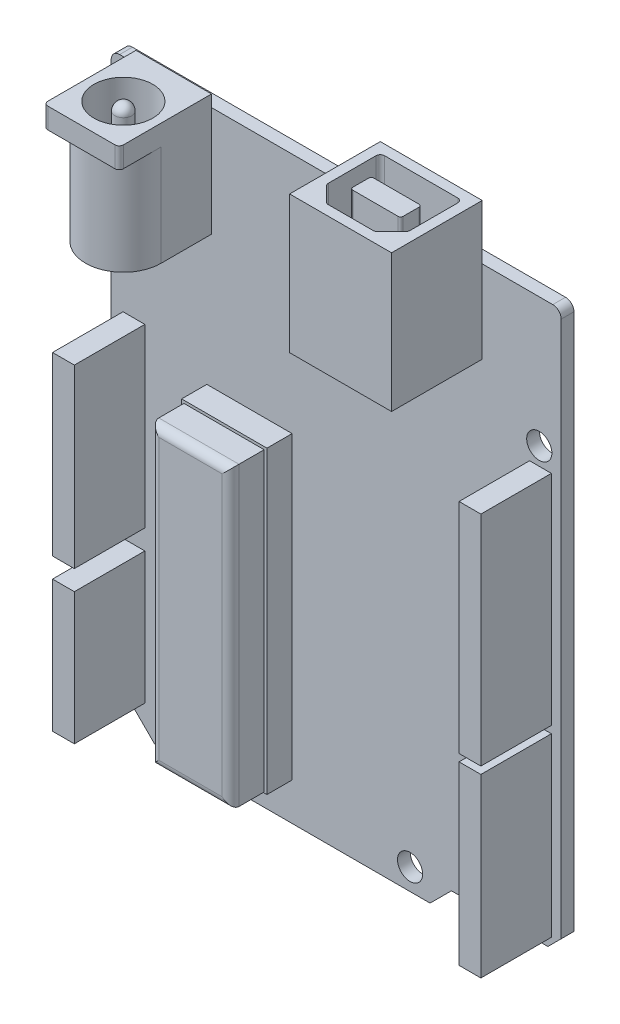
SolidWorks part; units mm, degrees
ref_plane "Plano frontal" through (0, 0, 0) normal (0, 0, 1) x (1, 0, 0)
ref_plane "Plano superior" through (0, 0, 0) normal (0, 1, 0) x (1, 0, 0)
ref_plane "Plano direito" through (0, 0, 0) normal (1, 0, 0) x (0, 0, -1)
sketch "Esboço1" plane through (0, 0, 0) normal (0, 0, 1) x (1, 0, 0)
  line L0 (391.5814, 45.9943) -> (391.5814, -648.0057) construction
  line L1 (25.8, 34.15) -> (-25.8, 34.15)
  line L2 (26.8, 33.15) -> (26.8, -30.7774)
  line L3 (-24.164, -32.36) -> (-25.8, -32.36)
  line L4 (-26.8, 33.15) -> (-26.8, -31.36)
  line L6 (-24.164, -32.36) -> (-21.6183, -34.9057)
  line L7 (11.1815, -34.9057) -> (-21.6183, -34.9057)
  line L10 (90.4669, 304.2448) -> (571.8003, 304.2448) construction
  line L11 (-23.855, 35.553) -> (-14.8521, 35.553)
  line L12 (-23.855, 35.553) -> (-23.855, 21.089)
  line L13 (-23.855, 21.089) -> (-14.8521, 21.089)
  line L14 (-14.8521, 35.553) -> (-14.8521, 21.089)
  line L15 (17.3958, 40.6929) -> (5.2524, 40.6929)
  line L16 (17.3958, 40.6929) -> (17.3958, 24.3152)
  line L17 (17.3958, 24.3152) -> (5.2524, 24.3152)
  line L18 (5.2524, 40.6929) -> (5.2524, 24.3152)
  line L19 (13.7272, -32.36) -> (11.1815, -34.9057)
  line L20 (25.2175, -32.36) -> (13.7272, -32.36)
  line L21 (26.8, -30.7774) -> (25.2175, -32.36)
  circle A0 centre (-24.164, 19.9912) radius 1.5
  circle A1 centre (24.1898, 18.7701) radius 1.5
  arc A2 (-26.8, -31.36) -> (-25.8, -32.36) centre (-25.8, -31.36) ccw
  circle A3 centre (-19.1491, -32.36) radius 1.5
  arc A4 (25.8, 34.15) -> (26.8, 33.15) centre (25.8, 33.15) cw
  arc A5 (-25.8, 34.15) -> (-26.8, 33.15) centre (-25.8, 33.15) ccw
  circle A6 centre (8.8002, -32.36) radius 1.5
  point P0 (0, 0)
  point P18 (26.8, 34.15)
  point P21 (-26.8, 34.15)
  dimension "D6" = 3
  dimension "D7" = 3
  dimension "D8" = 3
  dimension "D9" = 3
  dimension "D15" = 1
  dimension "D2" = 135
  dimension "D5" = 1
  dimension "D1" = 53.6
  dimension "D3" = 135
  dimension "D4" = 135
sketch "Esboço2" plane through (0, 0, 0) normal (0, 0, 1) x (1, 0, 0)
  line L0 (26.8, -30.7774) -> (25.2175, -32.36)
  line L1 (25.2175, -32.36) -> (13.7272, -32.36)
  line L2 (13.7272, -32.36) -> (11.1815, -34.9057)
  line L3 (11.1815, -34.9057) -> (-21.6183, -34.9057)
  line L4 (-21.6183, -34.9057) -> (-24.164, -32.36)
  line L5 (-24.164, -32.36) -> (-25.8, -32.36)
  line L7 (-26.8, -31.36) -> (-26.8, 33.15)
  line L9 (-25.8, 34.15) -> (25.8, 34.15)
  line L11 (26.8, 33.15) -> (26.8, -30.7774)
  arc A0 (26.8, 33.15) -> (25.8, 34.15) centre (25.8, 33.15) ccw
  arc A1 (-26.8, 33.15) -> (-25.8, 34.15) centre (-25.8, 33.15) cw
  arc A2 (-26.8, -31.36) -> (-25.8, -32.36) centre (-25.8, -31.36) ccw
  circle A3 centre (24.1898, 18.7701) radius 1.5
  circle A4 centre (-24.164, 19.9912) radius 1.5
  circle A5 centre (-19.1491, -32.36) radius 1.5
  circle A6 centre (8.8002, -32.36) radius 1.5
  dimension "D1" = 1
extrude "Ressalto-extrusão1" add sketch "Esboço2" along normal blind 1.52
sketch "Esboço3" plane through (0, 0, 1.52) normal (0, 0, 1) x (1, 0, 0)
  line L1 (-14.8521, 35.553) -> (-23.855, 35.553)
  line L2 (-14.8521, 35.553) -> (-14.8521, 21.089)
  line L3 (-14.8521, 21.089) -> (-23.855, 21.089)
  line L4 (-23.855, 35.553) -> (-23.855, 21.089)
extrude "Ressalto-extrusão2" add sketch "Esboço3" along normal blind 11
sketch "Esboço4" plane through (0, 0, 1.52) normal (0, 0, 1) x (1, 0, 0)
  line L1 (23.0345, -31.2018) -> (25.6345, -31.2018)
  line L2 (23.0345, -31.2018) -> (23.0345, -10.2018)
  line L3 (23.0345, -10.2018) -> (25.6345, -10.2018)
  line L4 (25.6345, -31.2018) -> (25.6345, -10.2018)
  line L8 (23.0345, -9.3418) -> (25.6345, -9.3418)
  line L9 (23.0345, -9.3418) -> (23.0345, 16.6582)
  line L10 (23.0345, 16.6582) -> (25.6345, 16.6582)
  line L11 (25.6345, -9.3418) -> (25.6345, 16.6582)
  line L13 (-25.392, 7.8156) -> (-22.792, 7.8156)
  line L14 (-25.392, 7.8156) -> (-25.392, -13.1844)
  line L15 (-25.392, -13.1844) -> (-22.792, -13.1844)
  line L16 (-22.792, 7.8156) -> (-22.792, -13.1844)
  line L17 (-22.792, -15.5599) -> (-25.392, -15.5599)
  line L18 (-22.792, -15.5599) -> (-22.792, -31.2599)
  line L19 (-22.792, -31.2599) -> (-25.392, -31.2599)
  line L20 (-25.392, -15.5599) -> (-25.392, -31.2599)
  dimension "D1" = 2.6
  dimension "D2" = 2.6
  dimension "D3" = 2.6
  dimension "D4" = 2.6
  dimension "D5" = 21
  dimension "D6" = 26
  dimension "D7" = 0.86
  dimension "D8" = 0
  dimension "D9" = 15.7
  dimension "D10" = 21
extrude "Ressalto-extrusão3" add sketch "Esboço4" along normal blind 8.4
sketch "Esboço5" plane through (0, 21.089, 0) normal (0, -1, 0) x (1, 0, 0)
  line L0 (-19.3536, 12.52) -> (-19.3536, 12.0214) construction
  line L3 (-14.8521, 7.52) -> (-14.8521, 12.52)
  line L5 (-14.8521, 12.52) -> (-23.855, 12.52)
  line L6 (-23.855, 12.52) -> (-23.855, 7.52)
  arc A0 (-14.8521, 7.52) -> (-23.855, 7.52) centre (-19.3536, 7.52) ccw
extrude "Corte-extrusão1" cut sketch "Esboço5" against normal blind 12
sketch "Esboço6" plane through (0, 35.553, 0) normal (0, -1, 0) x (1, 0, 0)
  circle A0 centre (-19.3536, 7.52) radius 3.5014
  circle A1 centre (-19.3536, 7.52) radius 1
  dimension "D1" = 7.0028
  dimension "D2" = 2
extrude "Corte-extrusão2" cut sketch "Esboço6" along normal blind 12
fillet "Filete1" radius 1 1 edges at (-19.3536, 35.553, 6.52)
fillet "Filete2" radius 0.5 2 edges at (-23.855, 34.321, 12.52) (-14.8521, 34.321, 12.52)
sketch "Esboço7" plane through (0, 0, 1.52) normal (0, 0, 1) x (1, 0, 0)
  line L1 (17.3958, 40.6929) -> (5.2524, 40.6929)
  line L2 (17.3958, 40.6929) -> (17.3958, 24.3152)
  line L3 (17.3958, 24.3152) -> (5.2524, 24.3152)
  line L4 (5.2524, 40.6929) -> (5.2524, 24.3152)
extrude "Ressalto-extrusão4" add sketch "Esboço7" along normal blind 10.8
sketch "Esboço8" plane through (0, 0, 1.52) normal (0, 0, -1) x (-1, 0, 0)
  line L0 (25.8, 34.15) -> (-25.8, 34.15) construction
  line L3 (0, 34.15) -> (0, -38.2715) construction
sketch "Esboço9" plane through (0, 40.6929, 0) normal (0, 1, 0) x (1, 0, 0)
  line L0 (17.3958, -12.32) -> (5.2524, -1.52) construction
  line L1 (17.3958, -12.32) -> (5.2524, -12.32) construction
  line L2 (6.9524, -2.72) -> (15.6958, -2.72)
  line L3 (6.4524, -3.22) -> (6.4524, -8.9129)
  line L4 (8.6595, -11.12) -> (13.9887, -11.12)
  line L5 (16.1958, -3.22) -> (16.1958, -8.9129)
  line L6 (6.4524, -2.72) -> (16.1958, -11.12) construction
  line L7 (6.4524, -11.12) -> (16.1958, -2.72) construction
  line L8 (5.2524, -12.32) -> (5.2524, -1.52) construction
  line L9 (14.3423, -10.9736) -> (16.0494, -9.2664)
  line L10 (14.0241, -8.17) -> (8.6241, -8.17)
  line L11 (14.3241, -7.87) -> (14.3241, -5.97)
  line L12 (14.0241, -5.67) -> (8.6241, -5.67)
  line L13 (8.3241, -7.87) -> (8.3241, -5.97)
  line L14 (14.3241, -8.17) -> (8.3241, -5.67) construction
  line L15 (14.3241, -5.67) -> (8.3241, -8.17) construction
  line L16 (6.5988, -9.2664) -> (8.3059, -10.9736)
  arc A0 (8.6241, -8.17) -> (8.3241, -7.87) centre (8.6241, -7.87) cw
  arc A1 (8.6241, -5.67) -> (8.3241, -5.97) centre (8.6241, -5.97) ccw
  arc A2 (14.3241, -5.97) -> (14.0241, -5.67) centre (14.0241, -5.97) ccw
  arc A3 (14.0241, -8.17) -> (14.3241, -7.87) centre (14.0241, -7.87) ccw
  arc A4 (6.9524, -2.72) -> (6.4524, -3.22) centre (6.9524, -3.22) ccw
  arc A5 (15.6958, -2.72) -> (16.1958, -3.22) centre (15.6958, -3.22) cw
  arc A6 (6.5988, -9.2664) -> (6.4524, -8.9129) centre (6.9524, -8.9129) cw
  arc A7 (8.3059, -10.9736) -> (8.6595, -11.12) centre (8.6595, -10.62) ccw
  arc A8 (14.3423, -10.9736) -> (13.9887, -11.12) centre (13.9887, -10.62) cw
  arc A9 (16.0494, -9.2664) -> (16.1958, -8.9129) centre (15.6958, -8.9129) ccw
  point P4 (11.3241, -6.92)
  point P13 (11.3241, -6.92)
  point P42 (6.4524, -9.12)
  point P45 (8.4524, -11.12)
  point P48 (14.1958, -11.12)
  point P51 (16.1958, -9.12)
  dimension "D5" = 0.3
  dimension "D6" = 0.5
  dimension "D7" = 0.5
  dimension "D1" = 1.2
  dimension "D2" = 1.2
  dimension "D3" = 6
  dimension "D4" = 2.5
extrude "Corte-extrusão3" cut sketch "Esboço9" against normal blind 10
sketch "Esboço10" plane through (0, 0, 1.52) normal (0, 0, 1) x (1, 0, 0)
  line L1 (-5.5812, 4.9919) -> (-15.136, 4.9919)
  line L2 (-5.5812, 4.9919) -> (-5.5812, -30.3202)
  line L3 (-5.5812, -30.3202) -> (-15.136, -30.3202)
  line L4 (-15.136, 4.9919) -> (-15.136, -30.3202)
extrude "Ressalto-extrusão5" add sketch "Esboço10" along normal blind 7
fillet "Filete3" radius 1 4 edges at (-10.3586, 4.9919, 8.52) (-5.5812, -12.6642, 8.52) (-10.3586, -30.3202, 8.52) (-15.136, -12.6642, 8.52)
sketch "Esboço11" plane through (0, 0, 1.52) normal (0, 0, 1) x (1, 0, 0)
  line L5 (-15.4124, -30.4213) -> (-5.2525, -30.4213)
  line L6 (-15.4124, -30.4213) -> (-15.4124, 5.3169)
  line L7 (-15.4124, 5.3169) -> (-5.2525, 5.3169)
  line L8 (-5.2525, -30.4213) -> (-5.2525, 5.3169)
  point P6 (-9.018, -5.9278)
extrude "Ressalto-extrusão6" add sketch "Esboço11" along normal blind 3
